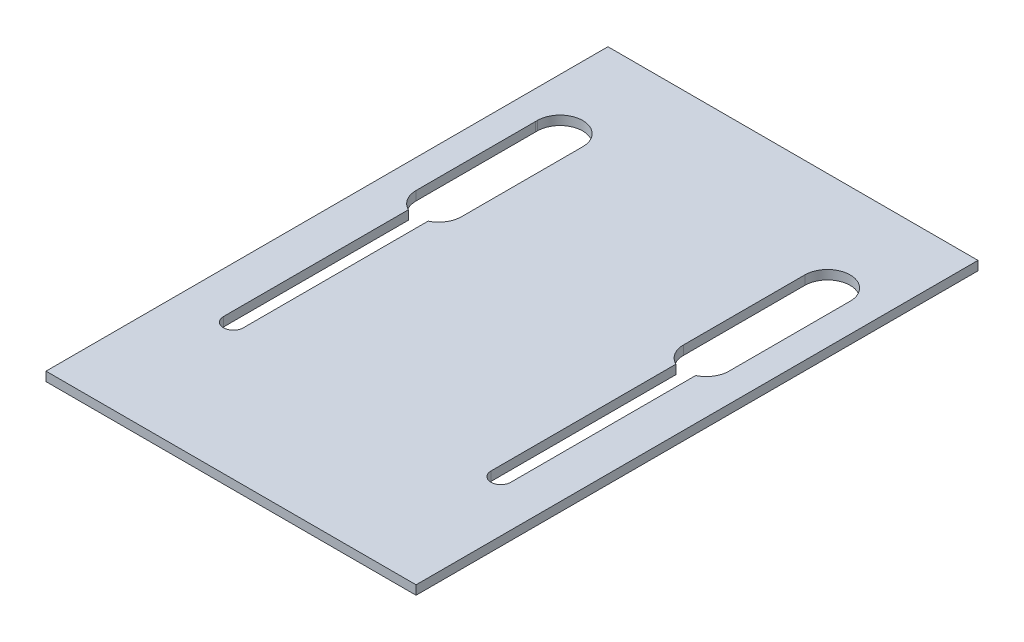
SolidWorks part; units mm, degrees
ref_plane "Front" through (0, 0, 0) normal (0, 0, 1) x (1, 0, 0)
ref_plane "Top" through (0, 0, 0) normal (0, 1, 0) x (1, 0, 0)
ref_plane "Right" through (0, 0, 0) normal (1, 0, 0) x (0, 0, -1)
sketch "Sketch3" plane through (0, 0, 0) normal (0, 1, 0) x (1, 0, 0)
  line L1 (0, 0) -> (122.1, 0)
  line L2 (0, 0) -> (0, 197.8)
  line L3 (0, 197.8) -> (122.1, 197.8)
  line L4 (122.1, 0) -> (122.1, 197.8)
  dimension "D1" = 122.1
  dimension "D2" = 197.8
extrude "Boss-Extrude2" add sketch "Sketch3" along normal blind 3
sketch "Sketch4" plane through (0, 3, 0) normal (0, 1, 0) x (1, 0, 0)
  line L1 (122.1, 197.8) -> (0, 197.8) construction
  line L2 (16.92, 145.3) -> (16.92, 45.3) construction
  line L3 (20.17, 145.3) -> (20.17, 45.3)
  line L4 (13.67, 145.3) -> (13.67, 45.3)
  line L8 (61.05, 197.8) -> (61.05, 0)
  line L9 (0, 0) -> (122.1, 0) construction
  line L13 (105.18, 145.3) -> (105.18, 45.3) construction
  line L14 (101.93, 145.3) -> (101.93, 45.3)
  line L15 (108.43, 145.3) -> (108.43, 45.3)
  line L16 (0, 197.8) -> (0, 0) construction
  circle A0 centre (16.92, 152.8) radius 7.5
  arc A1 (20.17, 145.3) -> (13.67, 145.3) centre (16.92, 145.3) ccw
  arc A2 (13.67, 45.3) -> (20.17, 45.3) centre (16.92, 45.3) ccw
  arc A9 (101.93, 145.3) -> (108.43, 145.3) centre (105.18, 145.3) cw
  arc A10 (108.43, 45.3) -> (101.93, 45.3) centre (105.18, 45.3) cw
  circle A11 centre (105.18, 152.8) radius 7.5
  point P8 (16.92, 95.3)
  point P37 (105.18, 95.3)
  dimension "D1" = 16.92
  dimension "D2" = 45
  dimension "D3" = 15
extrude "Cut-Extrude2" cut sketch "Sketch4" against normal blind 3 contours A1 A0
sketch "Sketch5" plane through (0, 0, -197.8) normal (0, 0, -1) x (-1, 0, 0)
  line L1 (30.4256, -53.051) -> (-155.2134, -53.051)
  line L2 (30.4256, -53.051) -> (30.4256, 40.7636)
  line L3 (30.4256, 40.7636) -> (-155.2134, 40.7636)
  line L4 (-155.2134, -53.051) -> (-155.2134, 40.7636)
extrude "Cut-Extrude3" cut sketch "Sketch5" against normal blind 12
sketch "Sketch7" plane through (0, 0, 0) normal (0, 0, 1) x (1, 0, 0)
  line L1 (-24.4421, 90.1889) -> (157.5298, 90.1889)
  line L2 (-24.4421, 90.1889) -> (-24.4421, -71.4208)
  line L3 (-24.4421, -71.4208) -> (157.5298, -71.4208)
  line L4 (157.5298, 90.1889) -> (157.5298, -71.4208)
extrude "Cut-Extrude4" cut sketch "Sketch7" against normal blind 19
sketch "Sketch8" plane through (0, 3, 0) normal (0, 1, 0) x (1, 0, 0)
  line L0 (16.9244, 153.0651) -> (16.9244, 113.0651) construction
  line L1 (24.4244, 153.0651) -> (24.4244, 113.0651)
  line L2 (9.4244, 153.0651) -> (9.4244, 113.0651)
  line L3 (61.05, 185.8) -> (61.05, 0)
  line L4 (0, 185.8) -> (122.1, 185.8) construction
  line L5 (105.1756, 153.0651) -> (105.1756, 113.0651) construction
  line L6 (97.6756, 153.0651) -> (97.6756, 113.0651)
  line L7 (112.6756, 153.0651) -> (112.6756, 113.0651)
  arc A0 (24.4244, 153.0651) -> (9.4244, 153.0651) centre (16.9244, 153.0651) ccw
  arc A1 (9.4244, 113.0651) -> (24.4244, 113.0651) centre (16.9244, 113.0651) ccw
  arc A2 (97.6756, 153.0651) -> (112.6756, 153.0651) centre (105.1756, 153.0651) cw
  arc A3 (112.6756, 113.0651) -> (97.6756, 113.0651) centre (105.1756, 113.0651) cw
  point P2 (16.9244, 133.0651)
  point P13 (105.1756, 133.0651)
  line M6 (20.17, 145.3) -> (20.17, 45.3)
  line M8 (13.67, 45.3) -> (13.67, 145.3)
  arc M9 (13.67, 145.3) -> (13.7472, 146.0042) centre (16.92, 145.3) cw
  arc M10 (13.7472, 146.0042) -> (20.0928, 146.0042) centre (16.92, 152.8) cw
  arc M11 (20.0928, 146.0042) -> (20.17, 145.3) centre (16.92, 145.3) cw
  line M13 (101.93, 45.3) -> (101.93, 145.3)
  arc M14 (101.93, 145.3) -> (102.0072, 146.0042) centre (105.18, 145.3) cw
  arc M15 (102.0072, 146.0042) -> (108.3528, 146.0042) centre (105.18, 152.8) cw
  arc M16 (108.3528, 146.0042) -> (108.43, 145.3) centre (105.18, 145.3) cw
  line M17 (108.43, 145.3) -> (108.43, 45.3)
extrude "Cut-Extrude8" cut sketch "Sketch8" against normal blind 10 contours A1 L2 M8 M6 M11 M10 M9 | A3 L7 A2 L6 M13 M14 M15 | A3 L7 M15 M16 M17 | L2 A1 M8 M9 M10 | A1 L1 A0 L2 M6 M10 M11
sketch "Sketch10" plane through (0, 0, -19) normal (0, 0, 1) x (1, 0, 0)
  line L1 (122.1, 3) -> (0, 3)
  line L2 (122.1, 3) -> (122.1, 0)
  line L3 (122.1, 0) -> (0, 0)
  line L4 (0, 3) -> (0, 0)
extrude "Boss-Extrude3" add sketch "Sketch10" along normal blind 18.6
